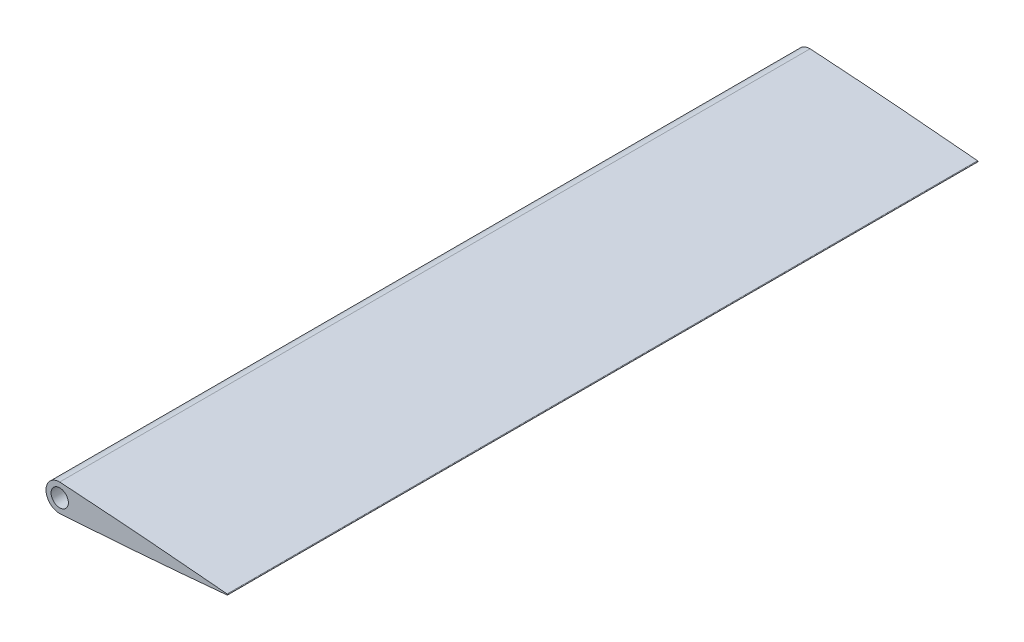
SolidWorks part; units mm, degrees
material "Foam"
ref_plane "Piano frontale" through (0, 0, 0) normal (0, 0, 1) x (1, 0, 0)
ref_plane "Piano superiore" through (0, 0, 0) normal (0, 1, 0) x (1, 0, 0)
ref_plane "Piano destro" through (0, 0, 0) normal (1, 0, 0) x (0, 0, -1)
curve "Curva1"
  spline degree 3 poles (100, 0.084, 0) (98.3335, 0.2367, 0) (95.0012, 0.5422, 0) (88.3356, 1.1109, 0) (80.0033, 1.7636, 0) (70.003, 2.4579, 0) (60.0031, 3.0617, 0) (50.003, 3.5521, 0) (40.0026, 3.9029, 0) (31.667, 4.0253, 0) (24.9992, 3.9769, 0) (19.9978, 3.845, 0) (14.9934, 3.5925, 0) (10.8272, 3.2377, 0) (7.4891, 2.814, 0) (4.9936, 2.4037, 0) (2.8496, 1.8679, 0) (1.1654, 1.321, 0) (-0.6646, 0, 0) (1.1654, -1.321, 0) (2.8496, -1.8679, 0) (4.9936, -2.4037, 0) (7.4891, -2.814, 0) (10.8272, -3.2377, 0) (14.9934, -3.5925, 0) (19.9978, -3.845, 0) (24.9992, -3.9769, 0) (31.667, -4.0253, 0) (40.0026, -3.9029, 0) (50.003, -3.5521, 0) (60.0031, -3.0617, 0) (70.003, -2.4579, 0) (80.0033, -1.7636, 0) (88.3356, -1.1109, 0) (95.0012, -0.5422, 0) (98.3335, -0.2367, 0) (100, -0.084, 0) knots 0 0 0 0 0.024876 0.049742 0.099443 0.149112 0.198751 0.248359 0.297937 0.347491 0.372267 0.397051 0.421859 0.446731 0.45922 0.471791 0.48456 0.491195 0.5 0.508805 0.51544 0.528209 0.54078 0.553269 0.578141 0.602949 0.627733 0.652509 0.702063 0.751641 0.801249 0.850888 0.900557 0.950258 0.975124 1 1 1 1
sketch "Schizzo1" plane through (0, 0, 0) normal (0, 0, 1) x (1, 0, 0)
  line L0 (71, 2.3776) -> (71, -2.3776) construction
  arc A0 (100, 0.084) -> (100, -0.084) centre (100, 0) cw
  arc A1 (71, 2.3776) -> (71, -2.3776) centre (71, 0) ccw
  spline S1 degree 3 poles (100, 0.084) (98.3335, 0.2367) (95.0012, 0.5422) (88.3356, 1.1109) (80.3363, 1.7375) (74.0008, 2.1802) (71, 2.3776) knots 0 0 0 0 0.024876 0.049742 0.099443 0.144147 0.144147 0.144147 0.144147
  spline S2 degree 3 poles (71, -2.3776) (74.0008, -2.1802) (80.3363, -1.7375) (88.3356, -1.1109) (95.0012, -0.5422) (98.3335, -0.2367) (100, -0.084) knots 0.855853 0.855853 0.855853 0.855853 0.900557 0.950258 0.975124 1 1 1 1
  spline S3 degree 3 poles (774.5938, 2905.893) (370.1816, -60.6448) (232.5901, -11.1972) (88.3356, 1.1109) (80.0033, 1.7636) (70.003, 2.4579) (60.0031, 3.0617) (50.003, 3.5521) (40.0026, 3.9029) (31.667, 4.0253) (24.9992, 3.9769) (19.9978, 3.845) (14.9934, 3.5925) (10.8272, 3.2377) (7.4891, 2.814) (4.9936, 2.4037) (2.8496, 1.8679) (1.1654, 1.321) (-0.6646, 0) (1.1654, -1.321) (2.8496, -1.8679) (4.9936, -2.4037) (7.4891, -2.814) (10.8272, -3.2377) (14.9934, -3.5925) (19.9978, -3.845) (24.9992, -3.9769) (31.667, -4.0253) (40.0026, -3.9029) (50.003, -3.5521) (60.0031, -3.0617) (70.003, -2.4579) (80.0033, -1.7636) (88.3356, -1.1109) (232.5893, 11.1971) (370.1799, 60.6442) (774.5865, -2905.8392) knots -2.052665 -2.052665 -2.052665 -2.052665 0.024876 0.049742 0.099443 0.149112 0.198751 0.248359 0.297937 0.347491 0.372267 0.397051 0.421859 0.446731 0.45922 0.471791 0.48456 0.491195 0.5 0.508805 0.51544 0.528209 0.54078 0.553269 0.578141 0.602949 0.627733 0.652509 0.702063 0.751641 0.801249 0.850888 0.900557 0.950258 0.975124 3.052652 3.052652 3.052652 3.052652 only from (100, 0.084) to (100, -0.084) construction
  spline S4 degree 3 poles (100, 0.084) (98.3335, 0.2367) (95.0012, 0.5422) (88.3356, 1.1109) (80.0033, 1.7636) (70.003, 2.4579) (60.0031, 3.0617) (50.003, 3.5521) (40.0026, 3.9029) (31.667, 4.0253) (24.9992, 3.9769) (19.9978, 3.845) (14.9934, 3.5925) (10.8272, 3.2377) (7.4891, 2.814) (4.9936, 2.4037) (2.8496, 1.8679) (1.1654, 1.321) (-0.6646, 0) (1.1654, -1.321) (2.8496, -1.8679) (4.9936, -2.4037) (7.4891, -2.814) (10.8272, -3.2377) (14.9934, -3.5925) (19.9978, -3.845) (24.9992, -3.9769) (31.667, -4.0253) (40.0026, -3.9029) (50.003, -3.5521) (60.0031, -3.0617) (70.003, -2.4579) (80.0033, -1.7636) (88.3356, -1.1109) (95.0012, -0.5422) (98.3335, -0.2367) (100, -0.084) knots 0 0 0 0 0.024876 0.049742 0.099443 0.149112 0.198751 0.248359 0.297937 0.347491 0.372267 0.397051 0.421859 0.446731 0.45922 0.471791 0.48456 0.491195 0.5 0.508805 0.51544 0.528209 0.54078 0.553269 0.578141 0.602949 0.627733 0.652509 0.702063 0.751641 0.801249 0.850888 0.900557 0.950258 0.975124 1 1 1 1 construction
  dimension "D1" = 29
  dimension "D2" = 4.7553
  dimension "D3" = 0.168
extrude "CorpoFoam" add sketch "Schizzo1" along normal blind 130
sketch "Schizzo2" plane through (0, 0, 0) normal (0, 0, -1) x (-1, 0, 0)
  line L0 (-71, 2.3776) -> (-71, -2.3776) construction
  circle A0 centre (-71, 0) radius 1.5
  dimension "D1" = 3
extrude "ForoPerno" cut sketch "Schizzo2" against normal through all
